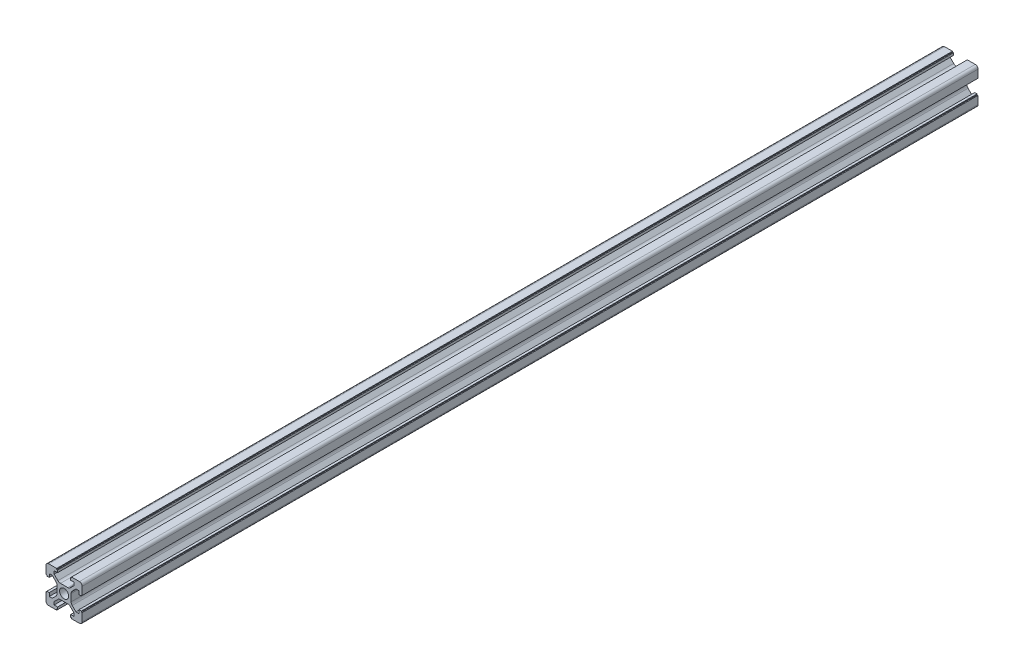
SolidWorks part; units mm, degrees
material "6063-O"
ref_plane "Front Plane" through (0, 0, 0) normal (0, 0, 1) x (1, 0, 0)
ref_plane "Top Plane" through (0, 0, 0) normal (0, 1, 0) x (1, 0, 0)
ref_plane "Right Plane" through (0, 0, 0) normal (1, 0, 0) x (0, 0, -1)
sketch "Sketch1" plane through (0, 0, 0) normal (0, 0, 1) x (1, 0, 0)
  line L0 (10, -4.1) -> (10, -8.5)
  line L1 (4.1, 10) -> (8.5, 10)
  line L2 (8.5, -10) -> (4.1, -10)
  line L3 (-8.5, -10) -> (-4.1, -10)
  line L4 (10, 8.5) -> (10, 4.1)
  line L7 (8.5, 10) -> (4.1, 10)
  line L8 (5.5, 6.5607) -> (3.4251, 4.4858)
  line L9 (8.5, 10) -> (4.1, 10)
  line L10 (3.9, 2.0109) -> (3.9, -2.0109)
  line L11 (2.0109, -3.9) -> (-2.0109, -3.9)
  line L12 (-3.9, -2.0109) -> (-3.9, 2.0109)
  line L13 (-2.0109, 3.9) -> (2.8393, 3.9)
  line L14 (2.5, 0) -> (22.2403, 0) construction
  line L15 (3.6, 9.5) -> (3.6, 8.2)
  line L16 (9.5, 3.6) -> (8.2, 3.6)
  line L17 (8.2, 3.6) -> (8.2, 5.5)
  line L18 (8.2, 5.5) -> (6.5607, 5.5)
  line L19 (10, -4.1) -> (10, -8.5)
  line L20 (4.1, 9.5) -> (3.6, 9.5)
  line L21 (4.1, 10) -> (4.1, 9.5)
  line L22 (8.5, 10) -> (4.1, 10)
  line L23 (10, 4.1) -> (9.5, 4.1)
  line L24 (9.5, 4.1) -> (9.5, 3.6)
  line L25 (5.5, 8.2) -> (5.5, 6.5607)
  line L26 (3.6, 8.2) -> (5.5, 8.2)
  line L27 (4.4858, 3.4251) -> (6.5607, 5.5)
  line L28 (10, -8.5) -> (10, -4.1)
  line L29 (6.5607, -5.5) -> (4.4858, -3.4251)
  line L30 (10, -8.5) -> (10, -4.1)
  line L31 (2.0109, -3.9) -> (-2.0109, -3.9)
  line L32 (3.9, 2.8393) -> (3.9, -2.0109)
  line L33 (9.5, -3.6) -> (8.2, -3.6)
  line L34 (3.6, -9.5) -> (3.6, -8.2)
  line L35 (3.6, -8.2) -> (5.5, -8.2)
  line L36 (5.5, -8.2) -> (5.5, -6.5607)
  line L37 (9.5, -4.1) -> (9.5, -3.6)
  line L38 (10, -4.1) -> (9.5, -4.1)
  line L39 (10, -8.5) -> (10, -4.1)
  line L40 (4.1, -10) -> (4.1, -9.5)
  line L41 (4.1, -9.5) -> (3.6, -9.5)
  line L42 (8.2, -5.5) -> (6.5607, -5.5)
  line L43 (8.2, -3.6) -> (8.2, -5.5)
  line L44 (3.4251, -4.4858) -> (5.5, -6.5607)
  line L45 (-4.1, -10) -> (-8.5, -10)
  line L46 (-10, -8.5) -> (-10, -4.1)
  line L47 (-8.5, -10) -> (-4.1, -10)
  line L48 (-5.5, -6.5607) -> (-3.4251, -4.4858)
  line L49 (-8.5, -10) -> (-4.1, -10)
  line L50 (-3.9, -2.0109) -> (-3.9, 2.0109)
  line L51 (2.0109, -3.9) -> (-2.0109, -3.9)
  line L52 (-3.6, -9.5) -> (-3.6, -8.2)
  line L53 (-9.5, -3.6) -> (-8.2, -3.6)
  line L54 (-8.2, -3.6) -> (-8.2, -5.5)
  line L55 (-8.2, -5.5) -> (-6.5607, -5.5)
  line L56 (-4.1, -9.5) -> (-3.6, -9.5)
  line L57 (-4.1, -10) -> (-4.1, -9.5)
  line L58 (-8.5, -10) -> (-4.1, -10)
  line L59 (-10, -4.1) -> (-9.5, -4.1)
  line L60 (-9.5, -4.1) -> (-9.5, -3.6)
  line L61 (-5.5, -8.2) -> (-5.5, -6.5607)
  line L62 (-3.6, -8.2) -> (-5.5, -8.2)
  line L63 (-4.4858, -3.4251) -> (-6.5607, -5.5)
  line L64 (-10, 4.1) -> (-10, 8.5)
  line L65 (-8.5, 10) -> (-4.1, 10)
  line L66 (-10, 8.5) -> (-10, 4.1)
  line L67 (-6.5607, 5.5) -> (-4.4858, 3.4251)
  line L68 (-10, 8.5) -> (-10, 4.1)
  line L69 (-2.0109, 3.9) -> (2.0109, 3.9)
  line L70 (-3.9, -2.0109) -> (-3.9, 2.0109)
  line L71 (-9.5, 3.6) -> (-8.2, 3.6)
  line L72 (-3.6, 9.5) -> (-3.6, 8.2)
  line L73 (-3.6, 8.2) -> (-5.5, 8.2)
  line L74 (-5.5, 8.2) -> (-5.5, 6.5607)
  line L75 (-9.5, 4.1) -> (-9.5, 3.6)
  line L76 (-10, 4.1) -> (-9.5, 4.1)
  line L77 (-10, 8.5) -> (-10, 4.1)
  line L78 (-4.1, 10) -> (-4.1, 9.5)
  line L79 (-4.1, 9.5) -> (-3.6, 9.5)
  line L80 (-8.2, 5.5) -> (-6.5607, 5.5)
  line L81 (-8.2, 3.6) -> (-8.2, 5.5)
  line L82 (-3.4251, 4.4858) -> (-5.5, 6.5607)
  line L83 (4.1, -10) -> (8.5, -10)
  arc A0 (2.0109, -3.9) -> (3.4251, -4.4858) centre (2.0109, -5.9) cw
  arc A1 (4.4858, -3.4251) -> (3.9, -2.0109) centre (5.9, -2.0109) cw
  arc A2 (3.9, 2.0109) -> (4.4858, 3.4251) centre (5.9, 2.0109) cw
  arc A3 (2.0109, 3.9) -> (3.4251, 4.4858) centre (2.0109, 5.9) ccw
  arc A4 (-2.0109, 3.9) -> (-3.4251, 4.4858) centre (-2.0109, 5.9) cw
  arc A5 (-4.4858, 3.4251) -> (-3.9, 2.0109) centre (-5.9, 2.0109) cw
  arc A6 (-3.4251, -4.4858) -> (-2.0109, -3.9) centre (-2.0109, -5.9) cw
  arc A7 (-3.9, -2.0109) -> (-4.4858, -3.4251) centre (-5.9, -2.0109) cw
  circle A8 centre (0, 0) radius 2.5
  arc A9 (-8.5, -10) -> (-10, -8.5) centre (-8.5, -8.5) cw
  arc A10 (-10, 8.5) -> (-8.5, 10) centre (-8.5, 8.5) cw
  arc A11 (8.5, 10) -> (10, 8.5) centre (8.5, 8.5) cw
  arc A12 (8.5, -10) -> (10, -8.5) centre (8.5, -8.5) ccw
  point P0 (0, 0)
  point P86 (0, 0)
  point P107 (10, -10)
  dimension "D3" = 2
  dimension "D5" = 5
  dimension "D2" = 1.5
  dimension "D8" = 1.5
  dimension "D6" = 4
  dimension "D7" = 6.1
  dimension "D11" = 0.5
  dimension "D12" = 0.5
extrude "Boss-Extrude2" add sketch "Sketch1" along normal blind 495
